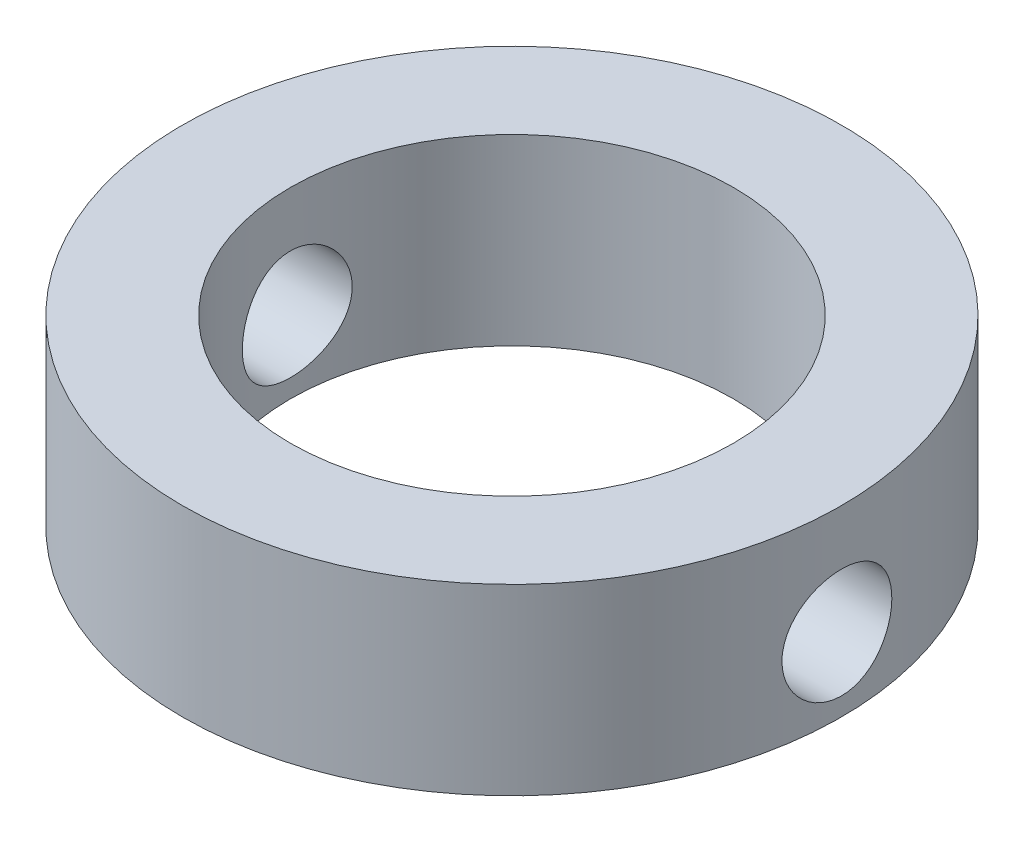
SolidWorks part; units mm, degrees
other "Front Axle Collar"
ref_plane "Front Plane" through (0, 0, 0) normal (0, 0, 1) x (1, 0, 0)
ref_plane "Top Plane" through (0, 0, 0) normal (0, 1, 0) x (1, 0, 0)
ref_plane "Right Plane" through (0, 0, 0) normal (1, 0, 0) x (0, 0, -1)
sketch3d "Collar stock sketch datum points"
  point P0 (-19.0092, -215, -53.2449)
  point P1 (-9.0092, -215, -53.2449)
  point P2 (-19.0092, -215, -63.2449)
ref_plane "Collar stock sketch plane" through (0, -215, 0) normal (0, 1, 0) x (1, 0, 0)
sketch "Collar stock sketch" plane through (0, -215, 0) normal (0, 1, 0) x (1, 0, 0)
  circle A0 centre (-19.0092, 53.2449) radius 9
extrude "Collar stock" add sketch "Collar stock sketch" along normal blind 5 separate body
sketch3d "Axle collar bore sketch datum points"
  point P0 (-19.0092, -215.1, -53.2449)
  point P1 (-9.0092, -215.1, -53.2449)
  point P2 (-19.0092, -215.1, -63.2449)
ref_plane "Axle collar bore sketch plane" through (0, -215.1, 0) normal (0, 1, 0) x (1, 0, 0)
sketch "Axle collar bore sketch" plane through (0, -215.1, 0) normal (0, 1, 0) x (1, 0, 0)
  circle A0 centre (-19.0092, 53.2449) radius 6.05
extrude "Axle collar bore" cut sketch "Axle collar bore sketch" along normal blind 5.2
sketch3d "Positive spring pin bore sketch datum points"
  point P0 (-29.0092, -213, -53.2449)
  point P1 (-29.0092, -203, -53.2449)
  point P2 (-29.0092, -213, -43.2449)
ref_plane "Positive spring pin bore sketch plane" through (-29.0092, 0, 0) normal (1, 0, 0) x (0, 0, -1)
sketch "Positive spring pin bore sketch" plane through (-29.0092, 0, 0) normal (1, 0, 0) x (0, 0, -1)
  circle A0 centre (53.2449, -213) radius 1.5
extrude "Positive spring pin bore" cut sketch "Positive spring pin bore sketch" along normal blind 20
